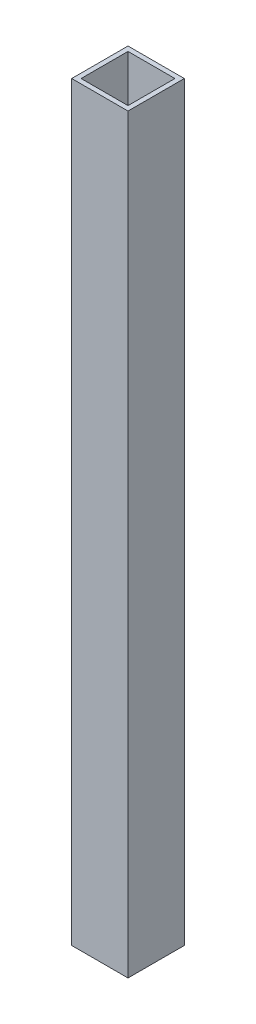
SolidWorks part; units mm, degrees
ref_plane "Front Plane" through (0, 0, 0) normal (0, 0, 1) x (1, 0, 0)
ref_plane "Top Plane" through (0, 0, 0) normal (0, 1, 0) x (1, 0, 0)
ref_plane "Right Plane" through (0, 0, 0) normal (1, 0, 0) x (0, 0, -1)
sketch "Sketch1" plane through (0, 0, 0) normal (0, 1, 0) x (1, 0, 0)
  line L1 (0, 0) -> (19.05, 0)
  line L2 (0, 0) -> (0, 19.05)
  line L3 (0, 19.05) -> (19.05, 19.05)
  line L4 (19.05, 0) -> (19.05, 19.05)
  dimension "D1" = 19.05
  dimension "D2" = 19.05
extrude "Extrude-Thin1" add sketch "Sketch1" along normal blind 254 thin thin type one direction reverse wall 1.5875
